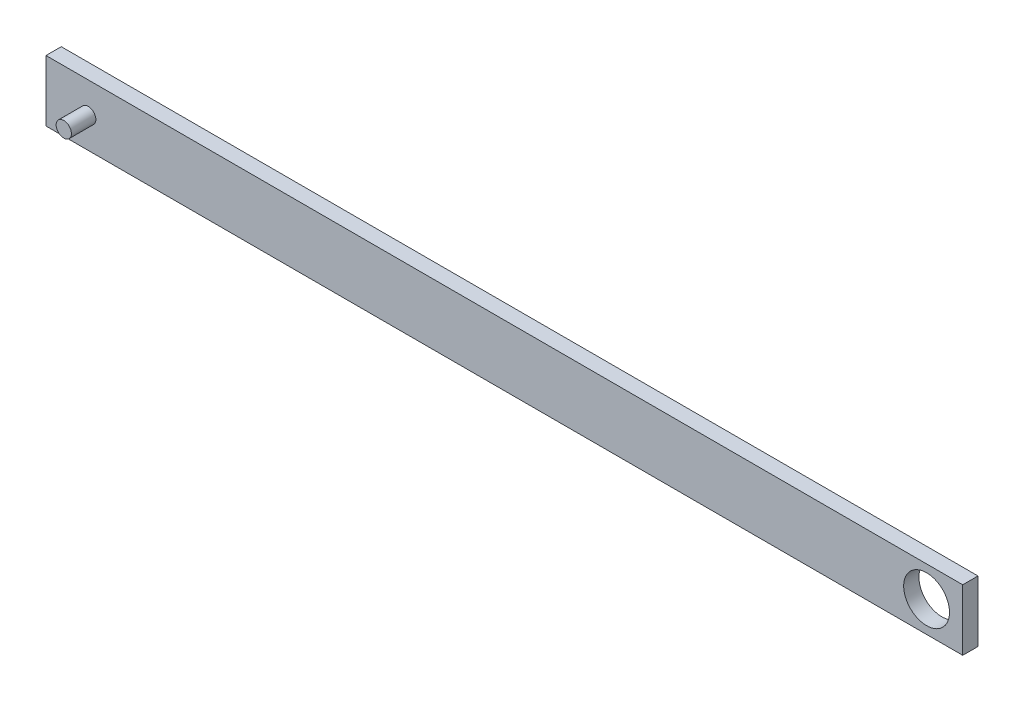
SolidWorks part; units mm, degrees
ref_plane "Front" through (0, 0, 0) normal (0, 0, 1) x (1, 0, 0)
ref_plane "Top" through (0, 0, 0) normal (0, 1, 0) x (1, 0, 0)
ref_plane "Right" through (0, 0, 0) normal (1, 0, 0) x (0, 0, -1)
sketch "Sketch1" plane through (0, 0, 0) normal (0, 0, 1) x (1, 0, 0)
  line L1 (150, -10) -> (-150, -10)
  line L2 (150, -10) -> (150, 10)
  line L3 (150, 10) -> (-150, 10)
  line L4 (-150, -10) -> (-150, 10)
  line L5 (150, -10) -> (-150, 10) construction
  line L6 (150, 10) -> (-150, -10) construction
  point P0 (0, 0)
  dimension "D1" = 300
  dimension "D2" = 20
extrude "Boss-Extrude1" add sketch "Sketch1" along normal blind 5
sketch "Sketch2" plane through (0, 0, 5) normal (0, 0, 1) x (1, 0, 0)
  circle A0 centre (138.173, 0) radius 7.5
  dimension "D1" = 15
extrude "Cut-Extrude1" cut sketch "Sketch2" against normal through all contours A0
sketch "Sketch3" plane through (0, 0, 5) normal (0, 0, 1) x (1, 0, 0)
  circle A0 centre (-136.1851, 0) radius 2.5
  dimension "D1" = 5
extrude "Boss-Extrude2" add sketch "Sketch3" along normal blind 8
